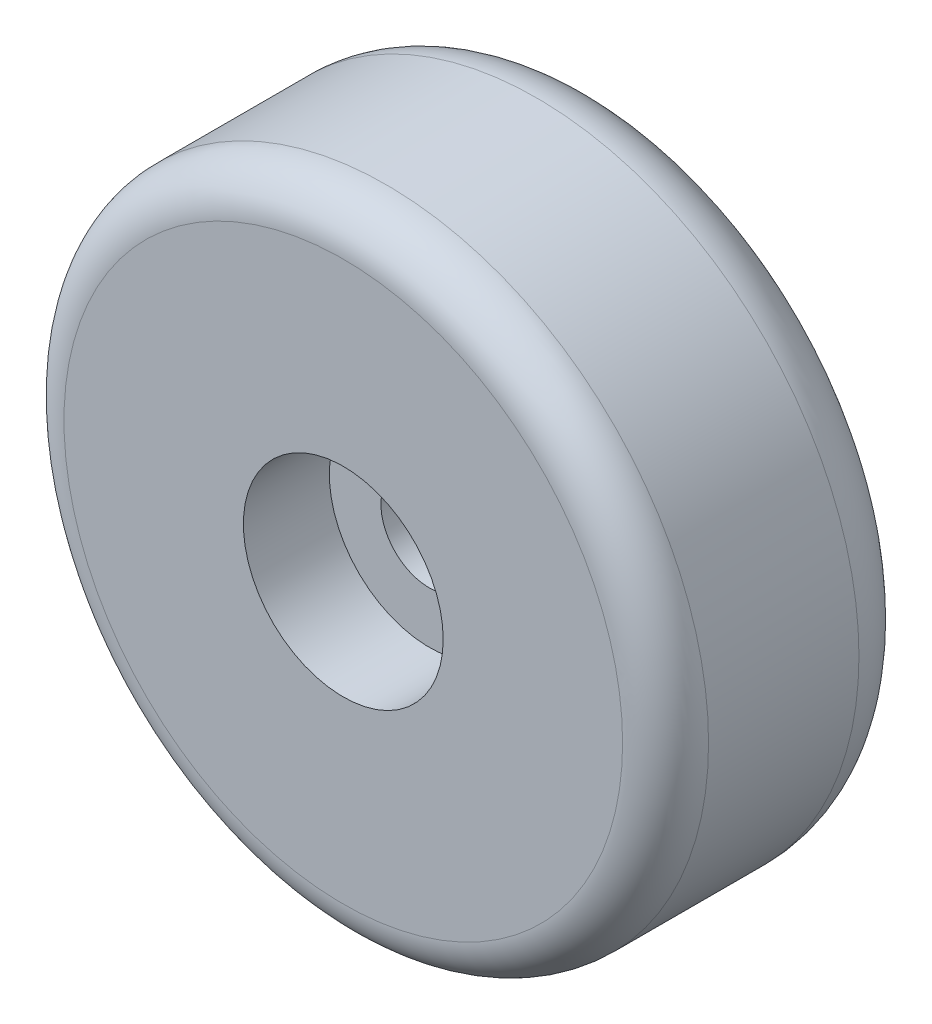
SolidWorks part; units mm, degrees
ref_plane "Спереди" through (0, 0, 0) normal (0, 0, 1) x (1, 0, 0)
ref_plane "Сверху" through (0, 0, 0) normal (0, 1, 0) x (1, 0, 0)
ref_plane "Справа" through (0, 0, 0) normal (1, 0, 0) x (0, 0, -1)
sketch "Эскиз1" plane through (0, 0, 0) normal (0, 0, 1) x (1, 0, 0)
  circle A0 centre (0, 0) radius 2.25
  circle A1 centre (0, 0) radius 15
  dimension "D1" = 4.5
  dimension "D2" = 30
extrude "Бобышка-Вытянуть1" add sketch "Эскиз1" along normal blind 12
sketch "Эскиз2" plane through (0, 0, 12) normal (0, 0, 1) x (1, 0, 0)
  circle A0 centre (0, 0) radius 4.65
  dimension "D1" = 9.3
extrude "Вырез-Вытянуть1" cut sketch "Эскиз2" against normal blind 4
fillet "Скругление1" radius 2 1 edges at (15, 0, 12)
fillet "Скругление2" radius 3 1 edges at (15, 0, 0)
